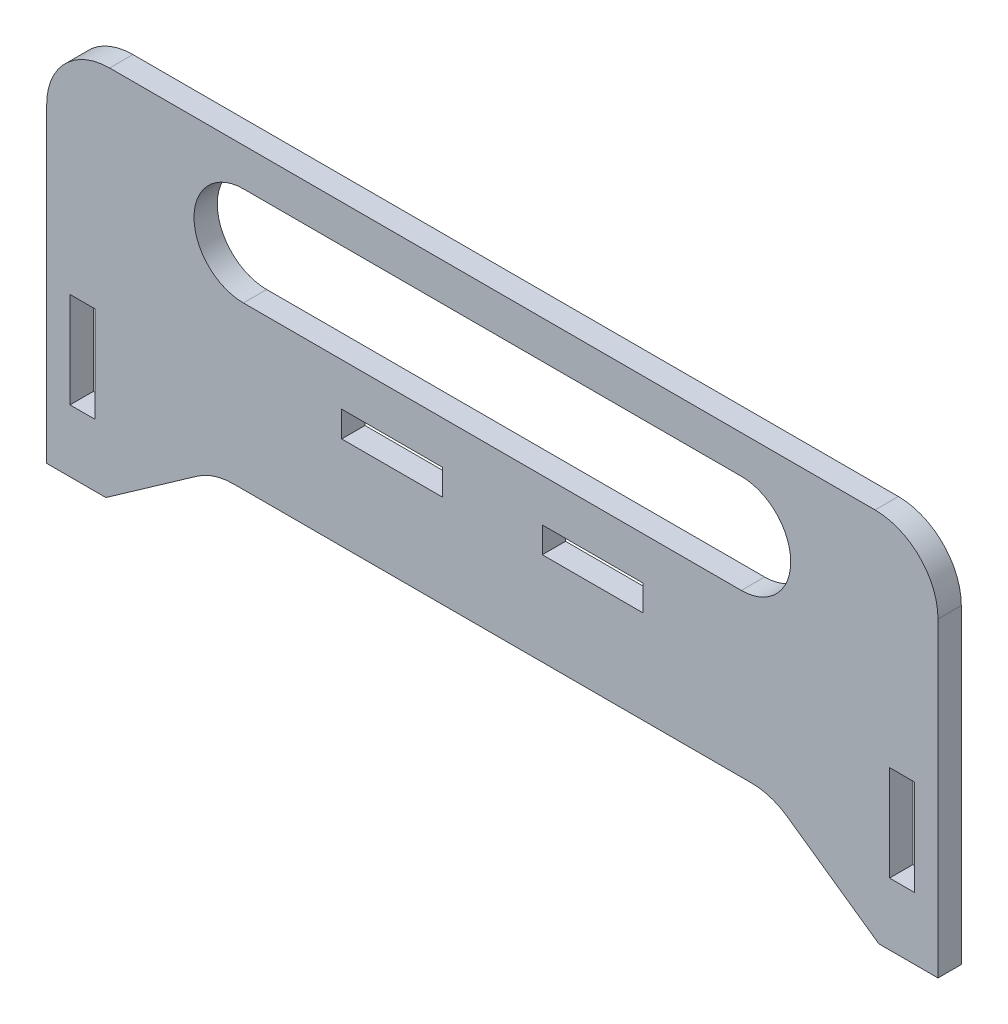
SolidWorks part; units mm, degrees
ref_plane "Front Plane" through (0, 0, 0) normal (0, 0, 1) x (1, 0, 0)
ref_plane "Top Plane" through (0, 0, 0) normal (0, 1, 0) x (1, 0, 0)
ref_plane "Right Plane" through (0, 0, 0) normal (1, 0, 0) x (0, 0, -1)
sketch "Sketch1" plane through (0, 0, 0) normal (0, 0, 1) x (1, 0, 0)
  line L0 (-110.1783, 0) -> (31.4217, 0)
  line L1 (31.4217, 0) -> (31.4217, -59.4)
  line L2 (-110.1783, 0) -> (-110.1783, -59.4)
  line L3 (-110.1783, -59.4) -> (-100.7783, -59.4)
  line L4 (-100.7783, -59.4) -> (-83.6783, -47.3833)
  line L5 (-83.6783, -47.3833) -> (4.9217, -47.3833)
  line L6 (4.9217, -47.3833) -> (22.0217, -59.4)
  line L7 (22.0217, -59.4) -> (31.4217, -59.4)
  line L8 (-39.3783, 0) -> (-39.3783, -94.7126) construction
  line L9 (-110.1783, -13.85) -> (31.4217, -13.85) construction
  line L10 (0.1717, -13.85) -> (-78.9283, -13.85) construction
  line L11 (0.1717, -21.7) -> (-78.9283, -21.7)
  line L12 (0.1717, -6) -> (-78.9283, -6)
  line L13 (-31.4458, -32.6) -> (-31.4458, -28.5)
  line L14 (-47.3108, -32.6) -> (-63.3108, -32.6)
  line L15 (-47.3108, -32.6) -> (-47.3108, -28.5)
  line L16 (-47.3108, -28.5) -> (-63.3108, -28.5)
  line L17 (-63.3108, -32.6) -> (-63.3108, -28.5)
  line L18 (-47.3108, -32.6) -> (-63.3108, -28.5) construction
  line L19 (-47.3108, -28.5) -> (-63.3108, -32.6) construction
  line L20 (-15.4458, -32.6) -> (-15.4458, -28.5)
  line L21 (-31.4458, -32.6) -> (-15.4458, -32.6)
  line L22 (-31.4458, -28.5) -> (-15.4458, -28.5)
  line L23 (27.7217, -49.5) -> (23.7217, -49.5)
  line L24 (-106.4783, -34.3) -> (-102.4783, -34.3)
  line L25 (-106.4783, -34.3) -> (-106.4783, -49.5)
  line L26 (-106.4783, -49.5) -> (-102.4783, -49.5)
  line L27 (-102.4783, -34.3) -> (-102.4783, -49.5)
  line L28 (-106.4783, -34.3) -> (-102.4783, -49.5) construction
  line L29 (-106.4783, -49.5) -> (-102.4783, -34.3) construction
  line L30 (23.7217, -34.3) -> (23.7217, -49.5)
  line L31 (27.7217, -34.3) -> (23.7217, -34.3)
  line L32 (27.7217, -34.3) -> (27.7217, -49.5)
  arc A0 (0.1717, -21.7) -> (0.1717, -6) centre (0.1717, -13.85) ccw
  arc A1 (-78.9283, -6) -> (-78.9283, -21.7) centre (-78.9283, -13.85) ccw
  point P15 (-39.3783, -13.85)
  point P20 (-86.7783, -13.85)
  point P21 (8.0217, -13.85)
  point P22 (-55.3108, -30.55)
  point P31 (-104.4783, -41.9)
  dimension "D1" = 59.4
  dimension "l" = 141.6
  dimension "D2" = 9.4
  dimension "D3" = 88.6
  dimension "D4" = 20.9
  dimension "D5" = 13.85
  dimension "D6" = 15.7
  dimension "D7" = 94.8
  dimension "D8" = 6.8
  dimension "D9" = 46.8675
  dimension "D10" = 16
  dimension "D11" = 4.1
  dimension "D12" = 9.9
  dimension "D13" = 3.7
  dimension "D14" = 4
  dimension "D15" = 15.2
extrude "Boss-Extrude2" add sketch "Sketch1" along normal blind 3.7
fillet "Fillet1" radius 10 2 edges at (-110.1783, 0, 1.85) (31.4217, 0, 1.85)
fillet "Fillet2" radius 10 2 edges at (4.9217, -47.3833, 1.85) (-83.6783, -47.3833, 1.85)
